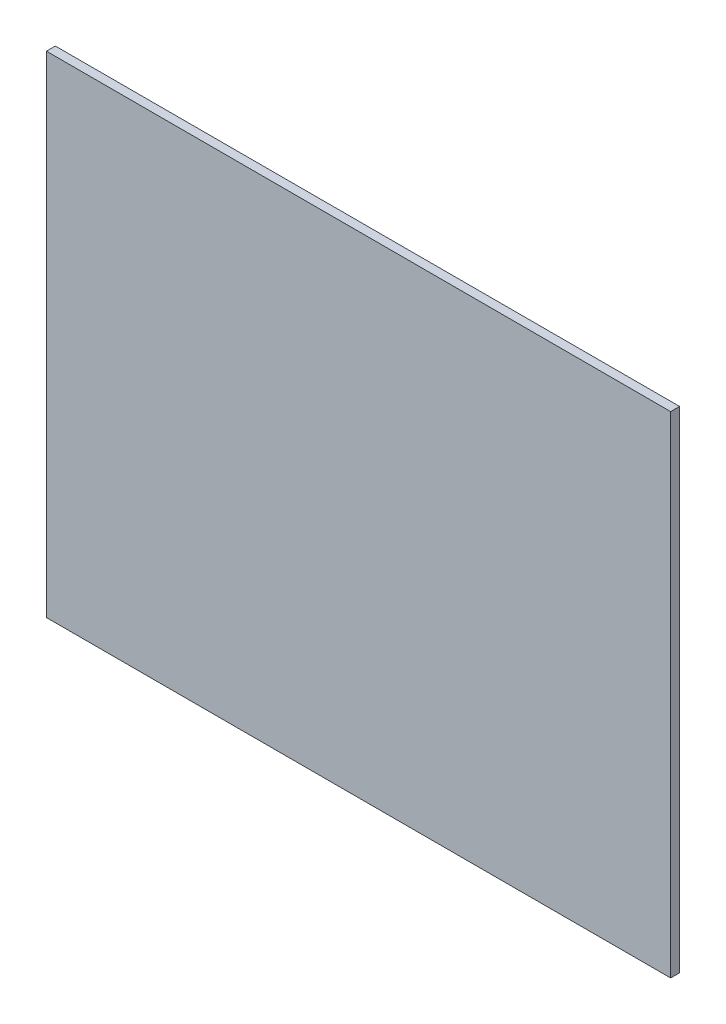
SolidWorks part; units mm, degrees
material "PC High Viscosity"
ref_plane "Front Plane" through (0, 0, 0) normal (0, 0, 1) x (1, 0, 0)
ref_plane "Top Plane" through (0, 0, 0) normal (0, 1, 0) x (1, 0, 0)
ref_plane "Right Plane" through (0, 0, 0) normal (1, 0, 0) x (0, 0, -1)
sketch "Sketch1" plane through (0, 0, 0) normal (0, 0, 1) x (1, 0, 0)
  line L1 (0, 0) -> (355.6, 0)
  line L2 (0, 0) -> (0, 279.4)
  line L3 (0, 279.4) -> (355.6, 279.4)
  line L4 (355.6, 0) -> (355.6, 279.4)
  dimension "D1" = 355.6
  dimension "D2" = 279.4
extrude "Boss-Extrude1" add sketch "Sketch1" along normal blind 5.08
